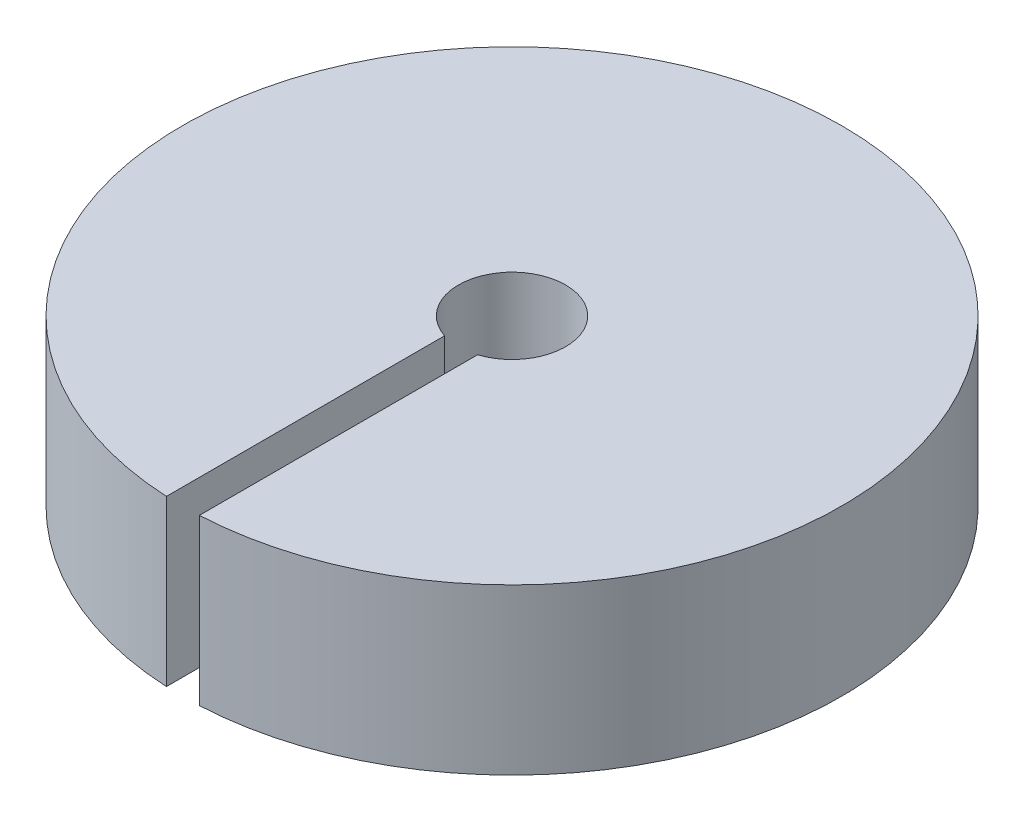
SolidWorks part; units mm, degrees
ref_plane "Front Plane" through (0, 0, 0) normal (0, 0, 1) x (1, 0, 0)
ref_plane "Top Plane" through (0, 0, 0) normal (0, 1, 0) x (1, 0, 0)
ref_plane "Right Plane" through (0, 0, 0) normal (1, 0, 0) x (0, 0, -1)
sketch "Sketch1" plane through (0, 0, 0) normal (0, 1, 0) x (1, 0, 0)
  line L1 (-1, -3.0923) -> (-1, -19.975)
  line L2 (1, -3.0923) -> (1, -19.975)
  arc A0 (1, -19.975) -> (-1, -19.975) centre (0, 0) ccw
  arc A1 (1, -3.0923) -> (-1, -3.0923) centre (0, 0) ccw
  dimension "D1" = 40
  dimension "D2" = 6.5
extrude "Boss-Extrude1" add sketch "Sketch1" along normal blind 10
